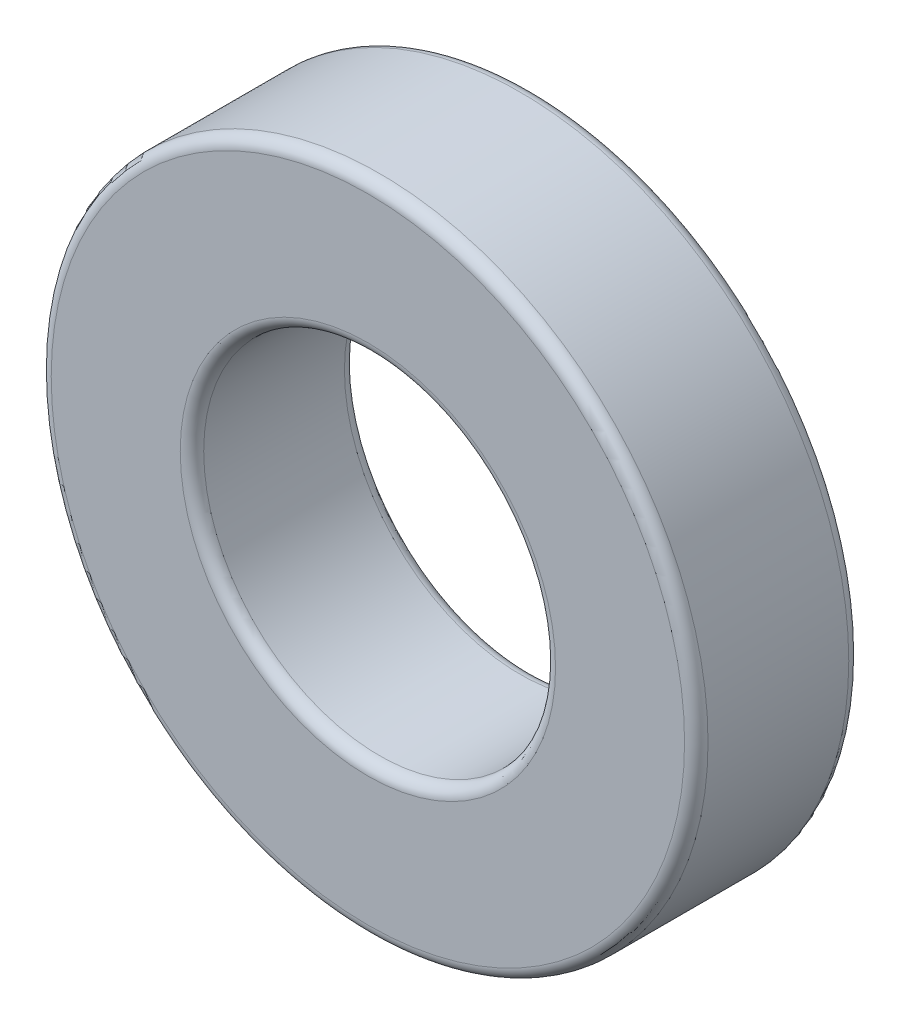
SolidWorks part; units mm, degrees
ref_plane "前视基准面" through (0, 0, 0) normal (0, 0, 1) x (1, 0, 0)
ref_plane "上视基准面" through (0, 0, 0) normal (0, 1, 0) x (1, 0, 0)
ref_plane "右视基准面" through (0, 0, 0) normal (1, 0, 0) x (0, 0, -1)
sketch "草图1" plane through (0, 0, 0) normal (0, 0, 1) x (1, 0, 0)
  circle A0 centre (0, 0) radius 14
  circle A1 centre (0, 0) radius 7.5
extrude "拉伸1" add sketch "草图1" along normal blind 7
fillet "圆角1" radius 0.5 4 edges at (14, 0, 0) (14, 0, 7) (7.5, 0, 0) (7.5, 0, 7)
